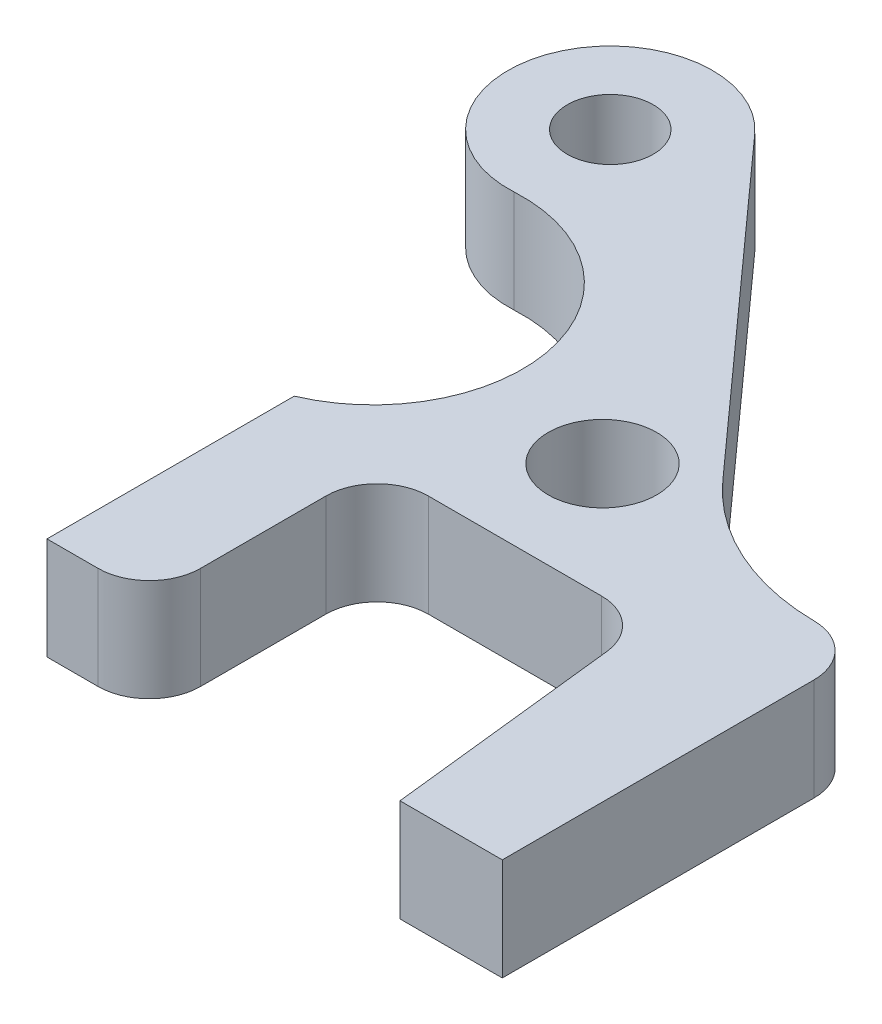
SolidWorks part; units mm, degrees
ref_plane "Front Plane" through (0, 0, 0) normal (0, 0, 1) x (1, 0, 0)
ref_plane "Top Plane" through (0, 0, 0) normal (0, 1, 0) x (1, 0, 0)
ref_plane "Right Plane" through (0, 0, 0) normal (1, 0, 0) x (0, 0, -1)
sketch "Sketch1" plane through (0, 0, 0) normal (0, 1, 0) x (1, 0, 0)
  line L0 (-27.6043, -11.39) -> (22.097, -11.39) construction
  line L1 (0, 0) -> (13.9511, -14.3306) construction
  line L2 (-44.4271, -7.39) -> (31.4032, -7.39) construction
  line L3 (-6, -6.0208) -> (-6, -11.39) construction
  line L4 (6, -11.39) -> (6, -6.0208) construction
  line L5 (-5.2905, 6.6529) -> (-2.1597, 9.1425) construction
  line L6 (6, -6.0208) -> (8.3016, -4.2566) construction
  circle A0 centre (0, -11.39) radius 4 construction
  circle A1 centre (0, 0) radius 6.5 construction
  circle A2 centre (13.9511, -14.3306) radius 2.5 construction
  circle A3 centre (0, 0) radius 2.5 construction
  arc A4 (-6, -6.0208) -> (-5.2905, 6.6529) centre (0, 0) cw construction
  arc A5 (-6, -11.39) -> (6, -11.39) centre (0, -11.39) ccw construction
  arc A6 (0, 0) -> (15.5762, 5.6033) centre (13.9511, -14.3306) cw construction
  arc A7 (-2.1597, 9.1425) -> (8.3016, -4.2566) centre (3.1308, 2.4896) cw construction
sketch "Sketch3" plane through (0, 0, 0) normal (0, 1, 0) x (-1, 0, 0)
  line L0 (-3.7183, -3.3428) -> (-17.6184, 12.1189)
  line L3 (-3.5617, 19.0057) -> (-3.5617, 31.0855)
  line L4 (-3.5617, 31.0855) -> (-6.0617, 31.0855)
  line L5 (-8.5617, 28.5855) -> (-8.5617, 22.4537)
  line L6 (-11.0617, 19.9537) -> (-19.5227, 19.9537)
  line L7 (-22.0074, 22.1779) -> (-23.2691, 33.5447)
  line L8 (-23.2691, 33.5447) -> (-28.2691, 33.5447)
  line L9 (-28.2691, 33.5447) -> (-28.2691, 18.3165)
  arc A0 (-3.7183, -3.3428) -> (-0.2918, 4.9915) centre (0, 0) ccw
  arc A1 (-0.2918, 4.9915) -> (-3.5617, 19.0057) centre (-0.6923, 12.2866) cw
  arc A2 (-6.0617, 31.0855) -> (-8.5617, 28.5855) centre (-6.0617, 28.5855) ccw
  arc A3 (-11.0617, 19.9537) -> (-8.5617, 22.4537) centre (-11.0617, 22.4537) ccw
  arc A4 (-19.5227, 19.9537) -> (-22.0074, 22.1779) centre (-19.5227, 22.4537) cw
  arc A5 (-17.6184, 12.1189) -> (-25.7961, 15.8167) centre (-25.9164, 4.659) ccw
  arc A6 (-25.7961, 15.8167) -> (-28.2691, 18.3165) centre (-25.7691, 18.3165) cw
  dimension "D2" = 5
  dimension "D3" = 2.5
  dimension "D4" = 2.5
  dimension "D5" = 2.5
  dimension "D6" = 2.5
  dimension "D8" = 11.1583
  dimension "D1" = 5
  dimension "D7" = 5
extrude "Boss-Extrude1" add sketch "Sketch3" against normal blind 5
hole_wizard "M5 Clearance Hole1" positions "Sketch5" profile "Sketch4" hole size "M5" standard "ISO" end condition through all
sketch "Sketch5" plane through (0, 0, 0) normal (0, 1, 0) x (-1, 0, 0)
  point P1 (-13.9511, 14.3306)
sketch "Sketch4" plane through (13.9511, 0, 14.3306) normal (1, 0, 0) x (0, 0, 1)
  line L0 (0, 0) -> (0, 5)
  line L1 (0, 5) -> (2.65, 5)
  line L2 (2.65, 5) -> (2.65, 0)
  line L5 (2.65, 0) -> (0, 0)
  line L11 (0, -6.35) -> (0, 107.95) construction
  dimension "Thru Hole Dia." = 5.3
  dimension "Thru Hole Depth" = 5
hole_wizard "M5 Tapped Hole1" positions "Sketch7" profile "Sketch6" tap size "M5" standard "ISO" end condition through all
sketch "Sketch7" plane through (0, 0, 0) normal (0, 1, 0) x (-1, 0, 0)
  point P0 (0, 0)
sketch "Sketch6" plane through (0, 0, 0) normal (1, 0, 0) x (0, 0, 1)
  line L0 (0, 0) -> (0, 5)
  line L1 (0, 5) -> (2.1, 5)
  line L2 (2.1, 5) -> (2.1, 0)
  line L5 (2.1, 0) -> (0, 0)
  line L11 (0, -6.35) -> (0, 107.95) construction
  dimension "Thru Tap Drill Dia." = 4.2
  dimension "Thru Tap Drill Depth" = 5
cosmetic thread "Hole Thread1" parameters "D2"=5
